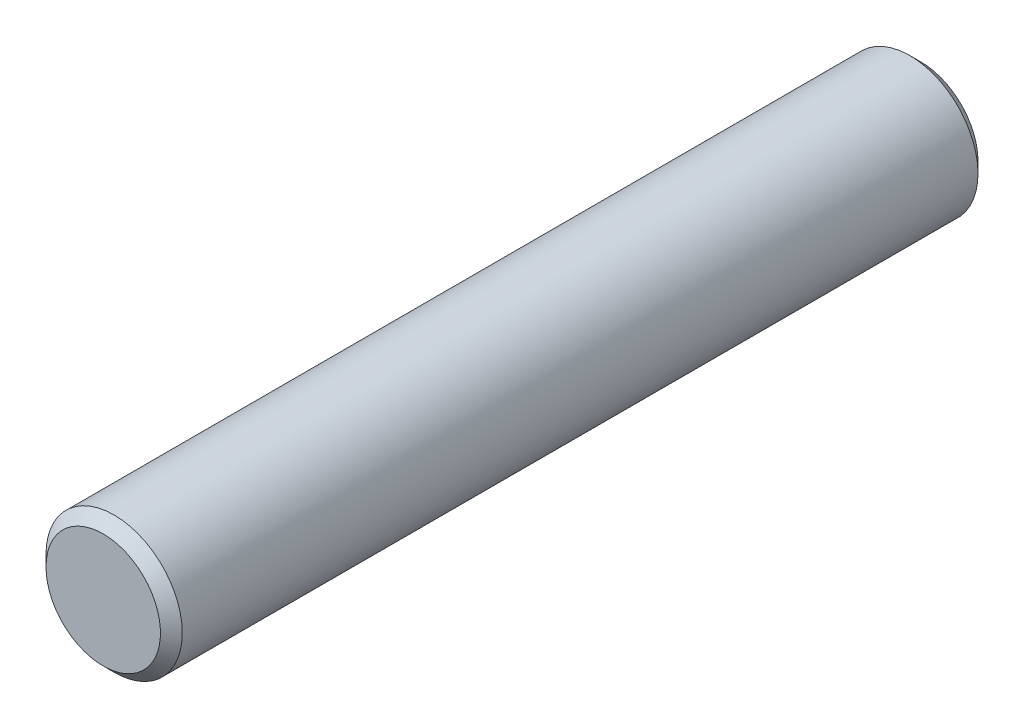
SolidWorks part; units mm, degrees
ref_plane "Front Plane" through (0, 0, 0) normal (0, 0, 1) x (1, 0, 0)
ref_plane "Top Plane" through (0, 0, 0) normal (0, 1, 0) x (1, 0, 0)
ref_plane "Right Plane" through (0, 0, 0) normal (1, 0, 0) x (0, 0, -1)
sketch "Sketch1" plane through (0, 0, 0) normal (1, 0, 0) x (0, 0, -1)
  line L0 (-12.3615, 0) -> (12.3615, 0) construction
  line L1 (-15, 2.5) -> (15, 2.5)
  line L2 (-15, 2.5) -> (-15, 0)
  line L3 (-15, 0) -> (15, 0)
  line L4 (15, 2.5) -> (15, 0)
  point P5 (0, 0)
  point P8 (0, 0)
  dimension "D1" = 5
  dimension "D3" = 30
revolve "Revolve1" add sketch "Sketch1" angle 360 about L0
chamfer "Chamfer1" distance 0.4 angle 45 2 edges at (2.5, 0, -15) (2.5, 0, 15)
